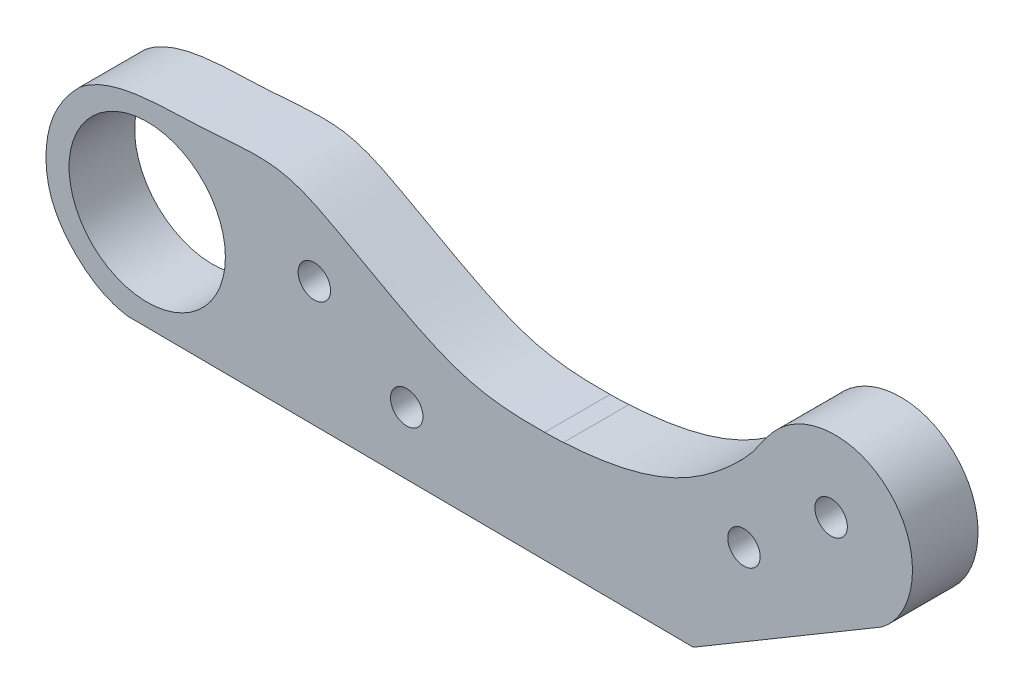
SolidWorks part; units mm, degrees
ref_plane "Piano frontale" through (0, 0, 0) normal (0, 0, 1) x (1, 0, 0)
ref_plane "Piano superiore" through (0, 0, 0) normal (0, 1, 0) x (1, 0, 0)
ref_plane "Piano destro" through (0, 0, 0) normal (1, 0, 0) x (0, 0, -1)
sketch "Schizzo2" plane through (0, 0, 0) normal (0, 0, 1) x (1, 0, 0)
  line L4 (-45.8065, 10.1385) -> (-29.7704, 19.6479)
  line L5 (-6.4285, 62.2183) -> (-12.7988, 61.6166)
  line L6 (-20.8222, 61.2865) -> (-45.448, 61.2865)
  line L7 (-89.3749, 10.4439) -> (-45.8065, 10.1385)
  line L8 (-45.8065, 10.1385) -> (-29.7704, 19.6479)
  line L9 (-6.4285, 62.2183) -> (-12.7988, 61.6166)
  line L10 (-20.8222, 61.2865) -> (-45.448, 61.2865)
  line L11 (-89.3749, 10.4439) -> (-45.8065, 10.1385)
  circle A0 centre (-74.9936, 19.9565) radius 1.7 construction
  circle A1 centre (-74.9936, 19.9565) radius 1.7 construction
  circle A2 centre (-35.1891, 24.1136) radius 1.7 construction
  circle A3 centre (-35.1891, 24.1136) radius 1.7 construction
  circle A4 centre (-87.8667, 18.1393) radius 6.02 construction
  circle A5 centre (-87.8667, 18.1393) radius 6.02
  circle A6 centre (-67.8766, 15.1106) radius 1.3935 construction
  circle A7 centre (-41.9032, 18.7531) radius 1.4054 construction
  ellipse E0 centre (-57.2563, 37.2981) end of major axis (-37.8063, 37.2981) minor radius 18.545 construction
  ellipse E1 centre (-57.2563, 37.2981) end of major axis (-37.8063, 37.2981) minor radius 18.545
  spline S0 degree 3 poles (-31.2793, 18.7531) (-29.098, 20.4037) (-27.9051, 25.4416) (-32.3004, 29.8584) (-36.6905, 29.9189) (-39.6149, 27.9424) (-41.0325, 25.5521) (-43.2846, 23.2416) (-48.1488, 19.5715) (-55.4824, 18.5532) (-63.1278, 18.896) (-68.3011, 21.4574) (-72.9856, 24.0866) (-76.3153, 25.8751) (-79.7395, 26.2367) (-83.2789, 25.795) (-88.2388, 25.8484) (-91.6892, 24.999) (-93.0837, 23.8512) knots 0 0 0 0 0.102244 0.160154 0.214293 0.256273 0.28915 0.319658 0.379342 0.518902 0.590345 0.669858 0.735081 0.798411 0.810363 0.866325 0.934004 1 1 1 1
  spline S3 degree 3 poles (-19121.6629, 19098.7032) (-167.8841, -116.7406) (-67.8079, -47.2085) (-19.5292, 31.9611) (-17.3272, 37.0506) (-14.922, 42.1161) (-12.0954, 46.687) (-8.8776, 49.9776) (-6.1277, 52.9833) (-2.8956, 55.0821) (-1.2594, 58.1768) (-20.5668, 103.2906) (-677.4947, -316.4063) (21566.368, -16123.5754) knots -4.657732 -4.657732 -4.657732 -4.657732 0.205065 0.292072 0.382852 0.505732 0.597107 0.672729 0.755685 0.8164 0.883587 0.921519 3.330237 3.330237 3.330237 3.330237 only from (-29.7704, 19.6479) to (-6.4285, 62.2183)
  spline S4 degree 3 poles (16277.7538, -21460.4397) (-68.9811, 182.0271) (-5.552, 73.2876) (-14.4957, 59.5279) (-16.4659, 58.2209) (-19.0371, 59.2045) (-26.2178, 74.3651) (-57.331, -71.0429) (-26501.535, -5157.2114) knots -4.560506 -4.560506 -4.560506 -4.560506 0.153142 0.247888 0.446916 0.809815 0.893165 5.180226 5.180226 5.180226 5.180226 only from (-12.7988, 61.6166) to (-20.8222, 61.2865)
  spline S5 degree 3 poles (-5356.9293, 26518.8286) (402.1576, -734.897) (103.4181, 99.1833) (-68.7052, 58.8464) (-73.7844, 57.362) (-77.6464, 56.2101) (-79.6123, 54.1168) (-79.7859, 51.8488) (-79.5708, 50.1209) (-79.8281, 48.2563) (-80.6297, 45.9722) (-81.574, 42.4408) (-82.9109, 38.1104) (-84.485, 33.6587) (-86.9307, 29.5959) (-89.5527, 26.432) (-93.1345, 24.132) (-95.2267, 21.2516) (-95.8242, 18.0471) (-95.4062, 15.1624) (-55.1812, -42.8234) (487.5691, 394.4166) (-516.6118, 26980.8345) knots -5.744793 -5.744793 -5.744793 -5.744793 0.193746 0.269881 0.346532 0.37765 0.40761 0.438995 0.45245 0.467917 0.503362 0.536032 0.594232 0.660243 0.698286 0.757936 0.800031 0.844688 0.876033 0.910905 0.942275 3.260891 3.260891 3.260891 3.260891 only from (-45.448, 61.2865) to (-89.3749, 10.4439)
  spline S6 degree 3 poles (-29.7704, 19.6479) (-26.177, 21.389) (-23.1961, 25.9479) (-19.5292, 31.9611) (-17.3272, 37.0506) (-14.922, 42.1161) (-12.0954, 46.687) (-8.8776, 49.9776) (-6.1277, 52.9833) (-2.8956, 55.0821) (-1.2594, 58.1768) (-2.6696, 61.4717) (-5.0083, 62.5113) (-6.4285, 62.2183) knots 0 0 0 0 0.205065 0.292072 0.382852 0.505732 0.597107 0.672729 0.755685 0.8164 0.883587 0.921519 1 1 1 1
  spline S7 degree 3 poles (-12.7988, 61.6166) (-13.4461, 61.691) (-13.6975, 60.756) (-14.4957, 59.5279) (-16.4659, 58.2209) (-19.0371, 59.2045) (-19.8762, 60.976) (-20.211, 61.2833) (-20.8222, 61.2865) knots 0 0 0 0 0.153142 0.247888 0.446916 0.809815 0.893165 1 1 1 1
  spline S8 degree 3 poles (-45.448, 61.2865) (-51.0279, 61.1688) (-58.9132, 61.1412) (-68.7052, 58.8464) (-73.7844, 57.362) (-77.6464, 56.2101) (-79.6123, 54.1168) (-79.7859, 51.8488) (-79.5708, 50.1209) (-79.8281, 48.2563) (-80.6297, 45.9722) (-81.574, 42.4408) (-82.9109, 38.1104) (-84.485, 33.6587) (-86.9307, 29.5959) (-89.5527, 26.432) (-93.1345, 24.132) (-95.2267, 21.2516) (-95.8242, 18.0471) (-95.4062, 15.1624) (-93.3152, 12.1482) (-91.0893, 10.6926) (-89.3749, 10.4439) knots 0 0 0 0 0.193746 0.269881 0.346532 0.37765 0.40761 0.438995 0.45245 0.467917 0.503362 0.536032 0.594232 0.660243 0.698286 0.757936 0.800031 0.844688 0.876033 0.910905 0.942275 1 1 1 1
  circle M8 centre (-74.9936, 19.9565) radius 1.7
  circle M9 centre (-35.1891, 24.1136) radius 1.7
  ellipse M11 centre (-57.2563, 37.2981) end of major axis (-37.8063, 37.2981) minor radius 18.545
  circle M14 centre (-87.8667, 18.1393) radius 6.02
  line M15 (-45.8065, 10.1385) -> (-29.7704, 19.6479)
  spline M20 degree 3 poles (-45.448, 61.2865) (-51.0279, 61.1688) (-58.9132, 61.1412) (-68.7052, 58.8464) (-73.7844, 57.362) (-77.6464, 56.2101) (-79.6123, 54.1168) (-79.7859, 51.8488) (-79.5708, 50.1209) (-79.8281, 48.2563) (-80.6297, 45.9722) (-81.574, 42.4408) (-82.9109, 38.1104) (-84.485, 33.6587) (-86.9307, 29.5959) (-89.5527, 26.432) (-93.1345, 24.132) (-95.2267, 21.2516) (-95.8242, 18.0471) (-95.4062, 15.1624) (-93.3152, 12.1482) (-91.0893, 10.6926) (-89.3749, 10.4439) knots 0 0 0 0 0.193746 0.269881 0.346532 0.37765 0.40761 0.438995 0.45245 0.467917 0.503362 0.536032 0.594232 0.660243 0.698286 0.757936 0.800031 0.844688 0.876033 0.910905 0.942275 1 1 1 1
  line M21 (-89.3749, 10.4439) -> (-45.8065, 10.1385)
  dimension "D1" = 0
extrude "Estrusione-Estrusione1" add sketch "Schizzo2" along normal blind 5.05 contours S0 M15 M11 M20 M21 M8 M14 M9 | M8 | M9
hole_wizard "Foro filettato M3x0.5-1" positions "Schizzo4" profile "Schizzo3" tap size "M3x0.5" standard "Ansi Metric" end condition through all
sketch "Schizzo4" plane through (0, 0, 5.05) normal (0, 0, 1) x (1, 0, 0)
  point P0 (-67.8766, 15.1106)
  point P3 (-74.9936, 19.9565)
  point P6 (-41.9032, 18.7531)
  point P9 (-35.1891, 24.1136)
sketch "Schizzo3" plane through (-67.8766, 15.1106, 5.05) normal (1, 0, 0) x (0, -1, 0)
  line L0 (0, 0) -> (0, 5.05)
  line L1 (0, 5.05) -> (1.25, 5.05)
  line L2 (1.25, 5.05) -> (1.25, 0)
  line L5 (1.25, 0) -> (0, 0)
  line L11 (0, -6.35) -> (0, 107.95) construction
  dimension "Thru Tap Drill Dia." = 2.5
  dimension "Thru Tap Drill Depth" = 5.05
cosmetic thread "Filettatura del foro1" parameters "D2"=3
cosmetic thread "Filettatura del foro2" parameters "D2"=3
cosmetic thread "Filettatura del foro3" parameters "D2"=3
cosmetic thread "Filettatura del foro4" parameters "D2"=3
